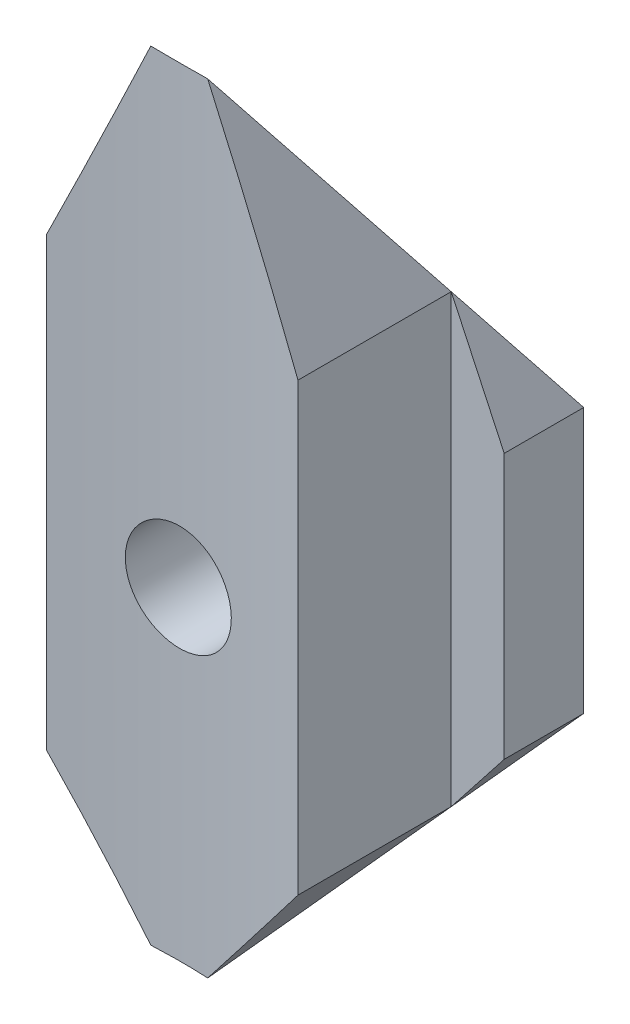
SolidWorks part; units mm, degrees
ref_plane "Front Plane" through (0, 0, 0) normal (0, 0, 1) x (1, 0, 0)
ref_plane "Top Plane" through (0, 0, 0) normal (0, 1, 0) x (1, 0, 0)
ref_plane "Right Plane" through (0, 0, 0) normal (1, 0, 0) x (0, 0, -1)
sketch "Sketch1" plane through (0, 0, 0) normal (0, 1, 0) x (1, 0, 0)
  line L10 (5, 0.5) -> (25, 0.5) construction
  line L11 (25, 0.5) -> (25, 20.5) construction
  line L12 (25, 20.5) -> (20, 25.5) construction
  line L13 (20, 25.5) -> (-20, 25.5) construction
  line L14 (-20, 25.5) -> (-25, 20.5) construction
  line L15 (-25, 20.5) -> (-25, 0.5) construction
  line L16 (-25, 0.5) -> (-5, 0.5) construction
  line L22 (-5, 0.5) -> (-5, 5) construction
  line L23 (-5, 5) -> (-10, 5) construction
  line L24 (5, 0.5) -> (5, 5) construction
  line L25 (5, 5) -> (10, 5) construction
  line L26 (-10, 5) -> (-10, 10.5) construction
  line L27 (-10, 10.5) -> (-7.5, 13) construction
  line L28 (-7.5, 13) -> (7.5, 13) construction
  line L29 (7.5, 13) -> (10, 10.5) construction
  line L30 (10, 10.5) -> (10, 5) construction
  line L31 (0, 25.5) -> (0, 0) construction
  line L32 (-4.75, -0.283) -> (-4.75, 5.5)
  line L33 (-4.75, 5.5) -> (-6.75, 5.5)
  line L34 (-6.75, 5.5) -> (-6.75, 8.5)
  line L35 (-6.75, 8.5) -> (6.75, 8.5)
  line L36 (6.75, 8.5) -> (6.75, 5.5)
  line L37 (6.75, 5.5) -> (4.75, 5.5)
  line L38 (4.75, 5.5) -> (4.75, -0.283)
  circle A0 centre (0, -40) radius 40 construction
  arc A1 (4.75, -0.283) -> (-4.75, -0.283) centre (0, -40) ccw
  point P23 (0, 25.5)
  point P25 (0, 13)
  point P30 (0, 0)
  dimension "D1" = 80
  dimension "D2" = 10
  dimension "D18" = 0.5
  dimension "D3" = 25
  dimension "D4" = 20
  dimension "D5" = 50
  dimension "D6" = 12.5
  dimension "D7" = 5
  dimension "D8" = 15
  dimension "D9" = 25
  dimension "D10" = 45
  dimension "D11" = 45
  dimension "D12" = 45
  dimension "D13" = 45
  dimension "D14" = 40
  dimension "D15" = 4.5
  dimension "D16" = 15
  dimension "D17" = 0.5
  dimension "D19" = 0.5
  dimension "D20" = 0.5
  dimension "D21" = 2
  dimension "D22" = 3
extrude "Boss-Extrude1" add sketch "Sketch1" along normal blind 30
sketch "Sketch2" plane through (6.75, 0, 0) normal (1, 0, 0) x (0, 0, -1)
  line L0 (-0.283, 30) -> (8.5, 17.4565)
  line L1 (8.5, 30) -> (8.5, 0) construction
  line L2 (8.5, 17.4565) -> (8.5, 7.4565)
  line L3 (8.5, 7.4565) -> (-0.283, 0)
  line L4 (-0.283, 0) -> (-0.283, 30)
  line L5 (-0.283, 30) -> (5.5, 30) construction
  dimension "D1" = 55
  dimension "D2" = 10
extrude "Cut-Extrude1" cut sketch "Sketch2" against normal blind 15 flip side to cut
sketch "Sketch3" plane through (0, 0, -8.5) normal (0, 0, -1) x (-1, 0, 0)
  line L0 (-6.75, 12.4565) -> (6.75, 12.4565) construction
  line L1 (-6.75, 17.4565) -> (-6.75, 7.4565) construction
  line L2 (6.75, 17.4565) -> (6.75, 7.4565) construction
  line L3 (-6.75, 17.4565) -> (-0.8946, 30)
  line L4 (-0.8946, 30) -> (0.8946, 30)
  line L5 (0.8946, 30) -> (6.75, 17.4565)
  line L6 (6.75, 17.4565) -> (6.75, 7.4565)
  line L7 (6.75, 7.4565) -> (0.8946, 0)
  line L8 (0.8946, 0) -> (-0.8946, 0)
  line L9 (-0.8946, 0) -> (-6.75, 7.4565)
  line L10 (-6.75, 7.4565) -> (-6.75, 17.4565)
  circle A0 centre (0, 12.4565) radius 2
  point P8 (0, 12.4565)
  point P12 (0, 30)
  point P23 (0, 0)
  dimension "D1" = 4
extrude "Cut-Extrude2" cut sketch "Sketch3" against normal blind 15 flip side to cut
